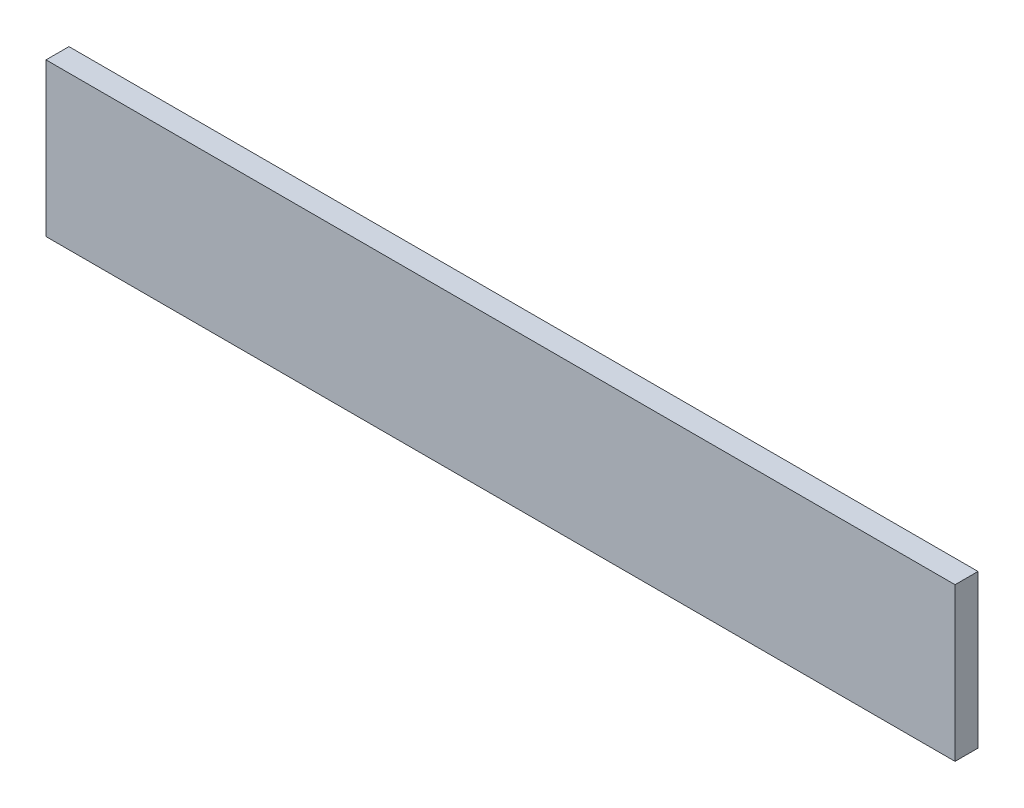
SolidWorks part; units mm, degrees
material "Cedro"
ref_plane "Alzado" through (0, 0, 0) normal (0, 0, 1) x (1, 0, 0)
ref_plane "Planta" through (0, 0, 0) normal (0, 1, 0) x (1, 0, 0)
ref_plane "Vista lateral" through (0, 0, 0) normal (1, 0, 0) x (0, 0, -1)
sketch "Croquis1" plane through (0, 0, 0) normal (1, 0, 0) x (0, 0, -1)
  line L1 (-7.5, -50) -> (7.5, -50)
  line L2 (-7.5, -50) -> (-7.5, 50)
  line L3 (-7.5, 50) -> (7.5, 50)
  line L4 (7.5, -50) -> (7.5, 50)
  line L5 (-7.5, -50) -> (7.5, 50) construction
  line L6 (-7.5, 50) -> (7.5, -50) construction
  point P0 (0, 0)
  dimension "D1" = 15
  dimension "D2" = 100
extrude "Saliente-Extruir1" add sketch "Croquis1" along normal blind 594
